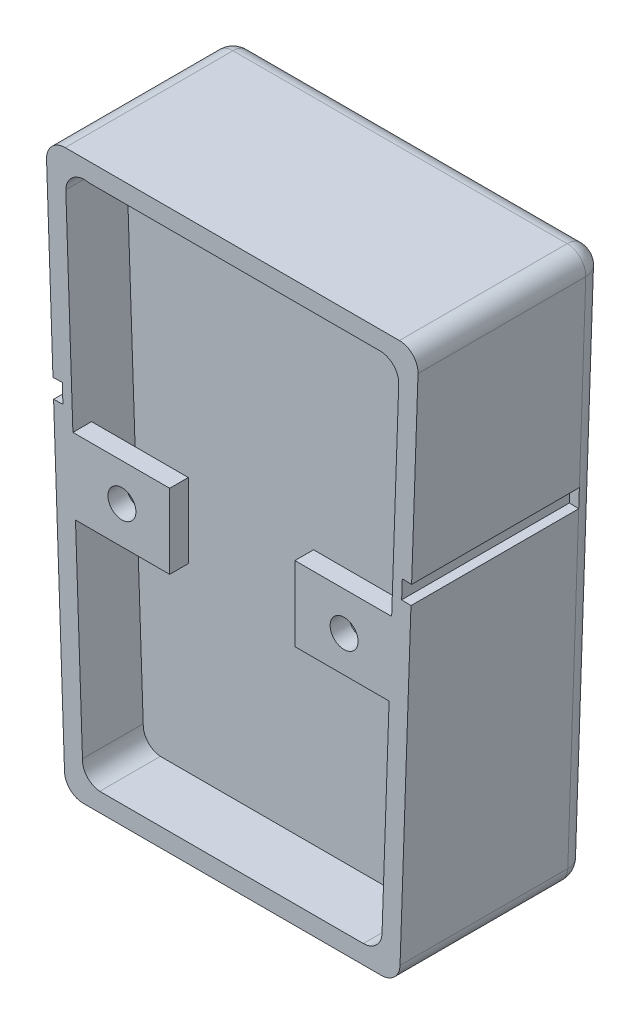
SolidWorks part; units mm, degrees
ref_plane "Front Plane" through (0, 0, 0) normal (0, 0, 1) x (1, 0, 0)
ref_plane "Top Plane" through (0, 0, 0) normal (0, 1, 0) x (1, 0, 0)
ref_plane "Right Plane" through (0, 0, 0) normal (1, 0, 0) x (0, 0, -1)
sketch "Sketch1" plane through (0, 0, 0) normal (0, 0, 1) x (1, 0, 0)
  line L8 (-22.7709, 76.1547) -> (22.7709, 76.1547)
  line L9 (25.3094, 73.5272) -> (22.8585, 2.4525)
  line L10 (20.32, 0) -> (-20.32, 0)
  line L11 (0, 76.1547) -> (0, 0) construction
  line L12 (-25.3094, 73.5272) -> (-22.8585, 2.4525)
  line L13 (-19.5413, 73.6147) -> (20.1418, 73.6147)
  line L14 (22.6803, 70.9872) -> (20.4046, 4.9925)
  line L15 (17.8661, 2.54) -> (-18.0612, 2.54)
  line L16 (-22.688, 71.2103) -> (-20.4122, 5.2126)
  arc A0 (22.8585, 2.4525) -> (20.32, 0) centre (20.32, 2.54) cw
  arc A1 (22.7709, 76.1547) -> (25.3094, 73.5272) centre (22.7709, 73.6147) cw
  arc A2 (-22.8585, 2.4525) -> (-20.32, 0) centre (-20.32, 2.54) ccw
  arc A3 (-22.7709, 76.1547) -> (-25.3094, 73.5272) centre (-22.7709, 73.6147) ccw
  circle A4 centre (0, 58.5396) radius 3.75
  circle A5 centre (0, 21.6223) radius 12.75
  arc A6 (20.4046, 4.9925) -> (17.8661, 2.54) centre (17.8661, 5.08) cw
  arc A7 (20.1418, 73.6147) -> (22.6803, 70.9872) centre (20.1418, 71.0747) cw
  arc A8 (-20.4122, 5.2126) -> (-18.0612, 2.54) centre (-17.876, 5.0732) ccw
  arc A9 (-19.5413, 73.6147) -> (-22.688, 71.2103) centre (-20.1487, 71.1484) ccw
  point P6 (22.7739, 0)
  point P9 (25.4, 76.1547)
  dimension "D2" = 76.2
  dimension "D3" = 2.54
  dimension "D5" = 7.5
  dimension "D6" = 24.7778
  dimension "D7" = 25.5
  dimension "D8" = 23.5056
  dimension "D12" = 2.54
  dimension "D13" = 2.54
  dimension "D15" = 2.54
  dimension "D1" = 25.4
  dimension "D4" = 40.64
  dimension "D9" = 65.9947
  dimension "D10" = 2.54
  dimension "D11" = 2.54
  dimension "D14" = 2.54
  dimension "D16" = 5.0732
  dimension "D17" = 5.2126
  dimension "D18" = 71.1484
  dimension "D19" = 71.2103
extrude "Boss-Extrude1" add sketch "Sketch1" along normal blind 3.81 contours L11 L13 A9 L16 A8 L15 A5 A4 | L13 L11 A4 A5 L15 A6 L14 A7 | L11 L8 A3 L12 A2 L10 L15 A8 L16 A9 L13 | L8 L11 L13 A7 L14 A6 L15 L10 A0 L9 A1
ref_plane "Plane1" through (0, 0, 3.81) normal (0, 0, 1) x (1, 0, 0)
sketch "Sketch4" plane through (0, 0, 3.81) normal (0, 0, 1) x (1, 0, 0)
  line L8 (-22.7709, 76.1547) -> (22.7709, 76.1547)
  line L9 (25.3094, 73.5272) -> (22.8585, 2.4525)
  line L10 (20.32, 0) -> (-20.32, 0)
  line L11 (0, 76.1547) -> (0, 0) construction
  line L12 (-25.3094, 73.5272) -> (-22.8585, 2.4525)
  line L13 (-19.5413, 73.6147) -> (20.1418, 73.6147)
  line L14 (22.6803, 70.9872) -> (20.4046, 4.9925)
  line L15 (17.8661, 2.54) -> (-18.0612, 2.54)
  line L16 (-22.688, 71.2103) -> (-20.4122, 5.2126)
  arc A0 (22.8585, 2.4525) -> (20.32, 0) centre (20.32, 2.54) cw
  arc A1 (22.7709, 76.1547) -> (25.3094, 73.5272) centre (22.7709, 73.6147) cw
  arc A2 (-22.8585, 2.4525) -> (-20.32, 0) centre (-20.32, 2.54) ccw
  arc A3 (-22.7709, 76.1547) -> (-25.3094, 73.5272) centre (-22.7709, 73.6147) ccw
  arc A6 (20.4046, 4.9925) -> (17.8661, 2.54) centre (17.8661, 5.08) cw
  arc A7 (20.1418, 73.6147) -> (22.6803, 70.9872) centre (20.1418, 71.0747) cw
  arc A8 (-20.4122, 5.2126) -> (-18.0612, 2.54) centre (-17.876, 5.0732) ccw
  arc A9 (-19.5413, 73.6147) -> (-22.688, 71.2103) centre (-20.1487, 71.1484) ccw
  point P6 (22.7739, 0)
  point P9 (25.4, 76.1547)
  dimension "D2" = 76.2
  dimension "D3" = 2.54
  dimension "D5" = 5.0732
  dimension "D6" = 5.2126
  dimension "D7" = 71.1484
  dimension "D8" = 71.2103
  dimension "D12" = 2.54
  dimension "D13" = 2.54
  dimension "D15" = 2.54
  dimension "D16" = 0
  dimension "D1" = 25.4
  dimension "D4" = 40.64
  dimension "D9" = 65.9947
  dimension "D10" = 2.54
  dimension "D11" = 2.54
  dimension "D14" = 2.54
extrude "Boss-Extrude3" add sketch "Sketch4" along normal blind 21.59
ref_plane "Plane2" through (0, 0, 14.605) normal (0, 0, 1) x (1, 0, 0)
sketch "Sketch7" plane through (0, 0, 14.605) normal (0, 0, 1) x (1, 0, 0)
  line L11 (0, 76.1547) -> (0, 0) construction
  line L13 (-19.5377, 73.6147) -> (20.1453, 73.6147)
  line L14 (22.6838, 70.9872) -> (20.4081, 4.9925)
  line L15 (17.8696, 2.54) -> (-18.0576, 2.54)
  line L16 (-22.6652, 71.1077) -> (-20.3894, 5.1099)
  line L17 (20.1418, 73.6147) -> (-19.5413, 73.6147) construction
  arc A6 (20.4081, 4.9925) -> (17.8696, 2.54) centre (17.8696, 5.08) cw
  arc A7 (20.1453, 73.6147) -> (22.6838, 70.9872) centre (20.1453, 71.0747) cw
  arc A8 (-20.3894, 5.1099) -> (-18.0576, 2.54) centre (-17.8497, 5.0715) ccw
  arc A9 (-19.5377, 73.6147) -> (-22.6652, 71.1077) centre (-20.1255, 71.1437) ccw
  point P6 (22.7739, 0)
  point P9 (25.4, 76.1547)
  dimension "D2" = 39.6831
  dimension "D3" = 65.9978
  dimension "D5" = 1.975
  dimension "D6" = 1.975
  dimension "D7" = 0
  dimension "D8" = 20.2239
  dimension "D12" = 2.54
  dimension "D13" = 2.54
  dimension "D15" = 2.54
  dimension "D11" = 20.1255
  dimension "D4" = 35.9272
  dimension "D9" = 65.9947
  dimension "D10" = 20.2012
extrude "Boss-Extrude4" add sketch "Sketch7" along normal blind 2.54
fillet "Fillet1" radius 2.54 8 edges at (0, 76.1547, 0) (-24.5976, 75.3796, 0) (-24.0839, 37.9898, 0) (-22.0848, 0.7133, 0) (0, 0, 0) (22.0848, 0.7133, 0) (24.0839, 37.9898, 0) (24.5976, 75.3796, 0)
sketch "Sketch8" plane through (0, 0, 25.4) normal (0, 0, 1) x (1, 0, 0)
  line L0 (-24.0839, 37.9898) -> (24.0839, 37.9898) construction
  line L1 (-25.3094, 73.5272) -> (-22.8585, 2.4525) construction
  line L2 (22.8585, 2.4525) -> (25.3094, 73.5272) construction
  line L3 (-21.3673, 32.9098) -> (-21.7176, 43.0698) construction
  line L4 (-22.688, 71.2103) -> (-20.4122, 5.2126) construction
  line L5 (-21.7176, 43.0698) -> (-8.5315, 43.0698)
  line L6 (-8.5315, 43.0698) -> (-8.5315, 32.9098)
  line L7 (-8.5315, 32.9098) -> (-21.3673, 32.9098)
  line L9 (0, 76.1547) -> (0, 0) construction
  line L10 (22.7709, 76.1547) -> (-22.7709, 76.1547) construction
  line L11 (-20.32, 0) -> (20.32, 0) construction
  line L12 (8.5315, 32.9098) -> (21.3673, 32.9098)
  line L13 (8.5315, 43.0698) -> (8.5315, 32.9098)
  line L14 (21.7176, 43.0698) -> (8.5315, 43.0698)
  line L15 (-21.3673, 32.9098) -> (-21.7176, 43.0698)
  line L16 (21.3673, 32.9098) -> (21.7176, 43.0698)
  dimension "D1" = 5.08
  dimension "D2" = 5.08
  dimension "D3" = 17.0629
extrude "Boss-Extrude6" add sketch "Sketch8" against normal blind 2.54
sketch "Sketch9" plane through (0, 0, 25.4) normal (0, 0, 1) x (1, 0, 0)
  line L0 (-15.1245, 43.0698) -> (-14.9494, 32.9098) construction
  line L1 (-8.5315, 43.0698) -> (-21.7176, 43.0698) construction
  line L2 (-21.3673, 32.9098) -> (-8.5315, 32.9098) construction
  line L3 (0.3003, 73.6147) -> (-0.0975, 2.54) construction
  line L4 (20.1418, 73.6147) -> (-19.5413, 73.6147) construction
  line L5 (-18.0612, 2.54) -> (17.8661, 2.54) construction
  circle A0 centre (-15.0369, 37.9898) radius 1.905
  circle A1 centre (15.2377, 37.8204) radius 1.905
  dimension "D1" = 3.81
extrude "Cut-Extrude1" cut sketch "Sketch9" against normal blind 2.54
sketch "Sketch10" plane through (0, 0, 0) normal (0, 0, -1) x (-1, 0, 0)
  line L0 (0, 73.6147) -> (0, 2.54) construction
  line L1 (22.7709, 73.6147) -> (-22.7709, 73.6147) construction
  line L2 (-20.32, 2.54) -> (20.32, 2.54) construction
  line L3 (-21.8533, 47.0045) -> (21.8533, 47.0045) construction
  line L4 (-22.7709, 73.6147) -> (-20.32, 2.54) construction
  line L5 (20.32, 2.54) -> (22.7709, 73.6147) construction
  line L6 (-21.8971, 48.2745) -> (21.8971, 48.2745)
  line L7 (21.8971, 48.2745) -> (21.8095, 45.7345)
  line L8 (21.8095, 45.7345) -> (-21.8095, 45.7345)
  line L9 (-21.8095, 45.7345) -> (-21.8971, 48.2745)
  dimension "D1" = 26.6102
  dimension "D2" = 1.27
  dimension "D3" = 1.27
extrude "Cut-Extrude2" cut sketch "Sketch10" against normal blind 1.27
sketch "Sketch11" plane through (-22.7469, -0.7844, 0) normal (-0.9994, -0.0345, 0) x (0, 0, 1)
  line L0 (2.54, 47.7456) -> (25.4, 47.7456) construction
  line L1 (2.54, 74.3558) -> (2.54, 3.2388) construction
  line L2 (25.4, 74.3558) -> (25.4, 3.2388) construction
  line L3 (25.4, 74.3558) -> (2.54, 74.3558) construction
  line L4 (2.54, 49.0156) -> (25.4, 49.0156)
  line L5 (25.4, 49.0156) -> (25.4, 46.4756)
  line L6 (25.4, 46.4756) -> (2.54, 46.4756)
  line L7 (2.54, 46.4756) -> (2.54, 49.0156)
  dimension "D1" = 26.6102
  dimension "D2" = 1.27
  dimension "D3" = 1.27
extrude "Cut-Extrude3" cut sketch "Sketch11" against normal blind 1.27
sketch "Sketch12" plane through (22.7469, -0.7844, 0) normal (0.9994, -0.0345, 0) x (0, 0, -1)
  line L0 (-25.4, 47.7456) -> (-2.54, 47.7456) construction
  line L1 (-25.4, 3.2388) -> (-25.4, 74.3558) construction
  line L2 (-2.54, 3.2388) -> (-2.54, 74.3558) construction
  line L3 (-25.4, 74.3558) -> (-2.54, 74.3558) construction
  line L4 (-2.54, 49.0156) -> (-25.4, 49.0156)
  line L5 (-25.4, 49.0156) -> (-25.4, 46.4756)
  line L6 (-25.4, 46.4756) -> (-2.54, 46.4756)
  line L7 (-2.54, 46.4756) -> (-2.54, 49.0156)
  dimension "D1" = 26.6102
  dimension "D2" = 1.27
  dimension "D3" = 1.27
extrude "Cut-Extrude4" cut sketch "Sketch12" against normal blind 1.27
